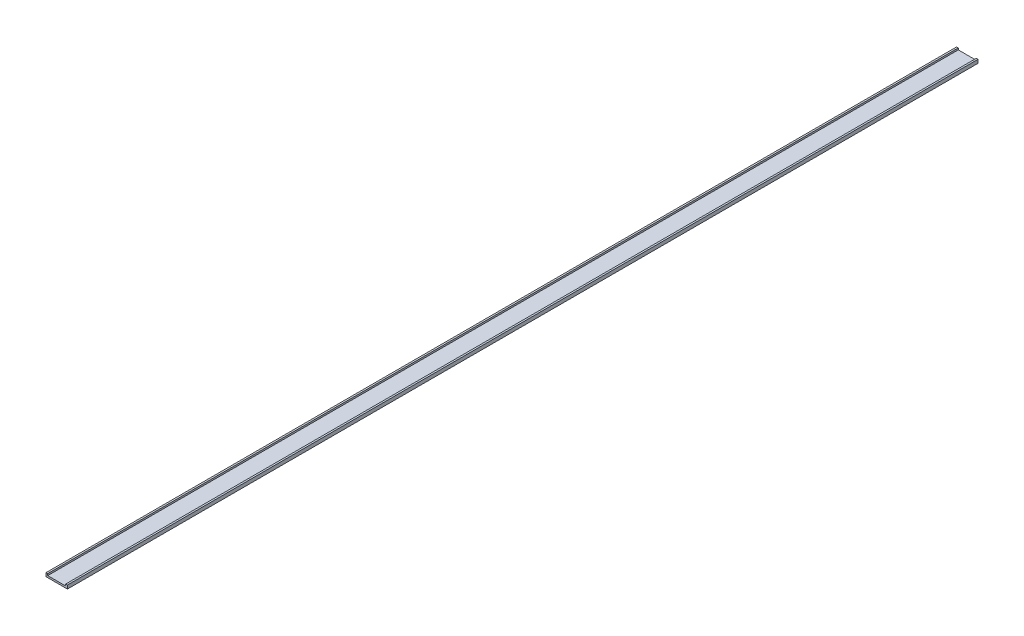
SolidWorks part; units mm, degrees
ref_plane "前视基准面" through (0, 0, 0) normal (0, 0, 1) x (1, 0, 0)
ref_plane "上视基准面" through (0, 0, 0) normal (0, 1, 0) x (1, 0, 0)
ref_plane "右视基准面" through (0, 0, 0) normal (1, 0, 0) x (0, 0, -1)
sketch "草图1" plane through (0, 0, 0) normal (0, 0, 1) x (1, 0, 0)
  line L0 (20, 0) -> (-20, 0)
  line L1 (-20, 0) -> (-20, 6.6)
  line L2 (-20, 6.6) -> (-16.8, 6.6)
  line L3 (-16.8, 6.6) -> (-16.8, 3.4)
  line L4 (-16.8, 3.4) -> (16.8, 3.4)
  line L5 (0, 13.656) -> (0, 0) construction
  line L6 (16.8, 6.6) -> (16.8, 3.4)
  line L7 (20, 6.6) -> (16.8, 6.6)
  line L8 (20, 0) -> (20, 6.6)
  point P9 (0, 3.4)
  dimension "D1" = 40
  dimension "D2" = 6.6
  dimension "D3" = 3.2
  dimension "D4" = 3.2
extrude "凸台-拉伸1" add sketch "草图1" along normal blind 1700
